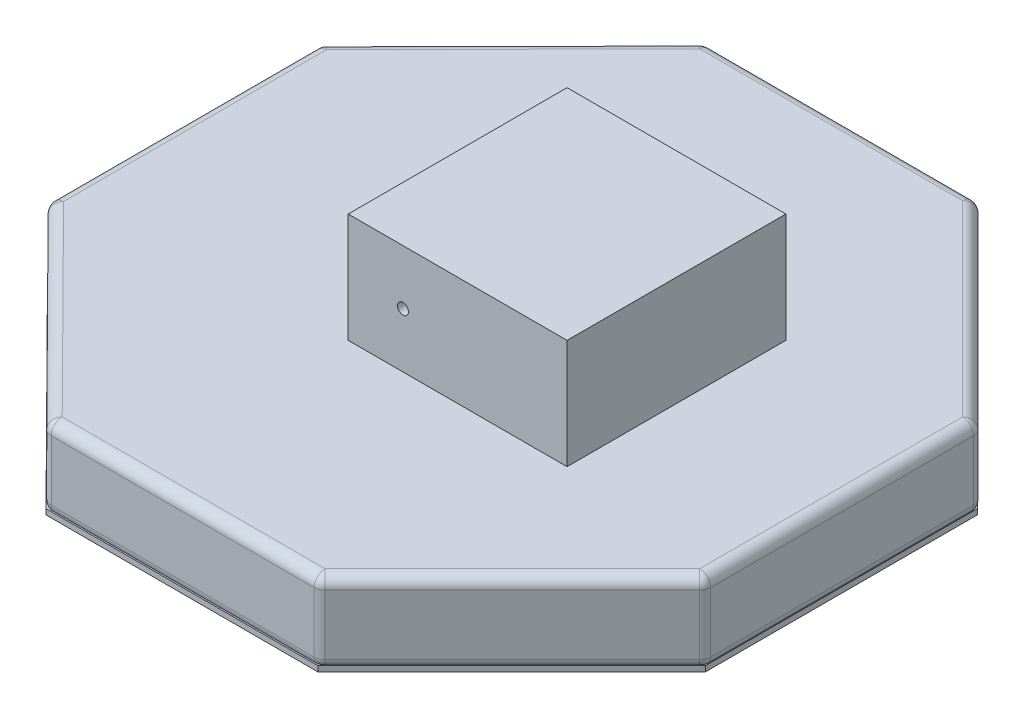
SolidWorks part; units mm, degrees
ref_plane "Front Plane" through (0, 0, 0) normal (0, 0, 1) x (1, 0, 0)
ref_plane "Top Plane" through (0, 0, 0) normal (0, 1, 0) x (1, 0, 0)
ref_plane "Right Plane" through (0, 0, 0) normal (1, 0, 0) x (0, 0, -1)
sketch "Sketch1" plane through (0, 0, 0) normal (0, 1, 0) x (1, 0, 0)
  line L5 (-60.1311, -24.8528) -> (-24.9839, -60.2623)
  line L6 (-24.9839, -60.2623) -> (24.7217, -60.2623)
  line L8 (24.7217, -60.2623) -> (60.1311, -24.8528)
  line L15 (60.1311, -24.8528) -> (60.1311, 24.8528)
  line L16 (24.7217, 60.2623) -> (60.1311, 24.8528)
  line L17 (-24.9839, 60.2623) -> (24.7217, 60.2623)
  line L18 (-60.1311, 24.8528) -> (-24.9839, 60.2623)
  line L19 (-60.1311, 24.8528) -> (-60.1311, -24.8528)
  point P0 (0, 0)
  point P1 (-0.1311, 0)
  point P2 (-0.1311, 0)
  point P3 (-0.1311, 0)
  point P4 (-0.1311, 0)
  point P6 (-0.1311, 0)
  point P9 (-42.5575, -42.5575)
  point P11 (-0.1311, -60.2623)
  point P13 (42.4264, -42.5575)
  point P15 (60.1311, 0)
  point P17 (42.4264, 42.5575)
  point P19 (-0.1311, 60.2623)
  point P20 (-42.5575, 42.5575)
  point P22 (-60.1311, 0)
  dimension "D1" = 135.213
  dimension "D2" = 135.213
  dimension "D3" = 225.213
  dimension "D4" = 225
  dimension "D6" = 135
  dimension "D5" = 135
  dimension "D7" = 49.7056
  dimension "D8" = 135
  dimension "D9" = 134.787
  dimension "D10" = 60.2623
sketch "Sketch2" plane through (0, 0, 0) normal (0, 1, 0) x (1, 0, 0)
  line L4 (-60, -24.8528) -> (-24.8528, -60.2623)
  line L5 (-24.8528, -60.2623) -> (24.8528, -60.2623)
  line L6 (24.8528, -60.2623) -> (60.2623, -24.8528)
  line L7 (60.2623, -24.8528) -> (60.2623, 24.8528)
  line L8 (24.8528, 60.2623) -> (60.2623, 24.8528)
  line L9 (-24.8528, 60.2623) -> (24.8528, 60.2623)
  line L10 (-60, 24.8528) -> (-24.8528, 60.2623)
  line L11 (-60, 24.8528) -> (-60, -24.8528)
  point P4 (0, 0)
  point P8 (0, 0)
  point P11 (0, 0)
  point P12 (0, 0)
  point P15 (0, 0)
  point P18 (-42.4264, -42.5575)
  point P21 (0, -60.2623)
  point P24 (42.5575, -42.5575)
  point P27 (60.2623, 0)
  point P30 (42.5575, 42.5575)
  point P33 (0, 60.2623)
  point P36 (-42.4264, 42.5575)
  point P39 (-60, 0)
  dimension "D5" = 135.213
  dimension "D6" = 135.213
  dimension "D8" = 225
  dimension "D10" = 135
  dimension "D11" = 49.7056
extrude "Boss-Extrude2" add sketch "Sketch2" along normal blind 15
sketch "Sketch3" plane through (0, 15, 0) normal (0, 1, 0) x (1, 0, 0)
  line L1 (30, -20) -> (-10, -20)
  line L2 (30, -20) -> (30, 20)
  line L3 (30, 20) -> (-10, 20)
  line L4 (-10, 20) -> (-10, -20)
  point P4 (0, 0)
extrude "Boss-Extrude3" add sketch "Sketch3" along normal blind 20
fillet "Fillet2" radius 2 24 edges at (42.5575, 15, -42.5575) (0, 15, -60.2623) (-42.4264, 15, -42.5575) (-60, 15, 0) (-60, 7.5, 24.8528) (-60, 7.5, -24.8528) (-24.8528, 7.5, -60.2623) (24.8528, 7.5, -60.2623) (60.2623, 7.5, -24.8528) (-42.4264, 15, 42.5575) (-24.8528, 7.5, 60.2623) (60.2623, 15, 0) (60.2623, 7.5, 24.8528) (42.5575, 15, 42.5575) (24.8528, 7.5, 60.2623) (0, 15, 60.2623) (42.5575, 0, -42.5575) (60.2623, 0, 0) (42.5575, 0, 42.5575) (-42.4264, 0, 42.5575) (0, 0, 60.2623) (-60, 0, 0) (-42.4264, 0, -42.5575) (0, 0, -60.2623)
sketch "Sketch4" plane through (0, 0, 20) normal (0, 0, 1) x (1, 0, 0)
  line L0 (0, 0) -> (0, 35) construction
  line L1 (-10, 35) -> (30, 35) construction
  line L2 (-10, 25) -> (30, 25) construction
  line L3 (-10, 35) -> (-10, 15) construction
  line L4 (30, 35) -> (30, 15) construction
  circle A0 centre (0, 25) radius 1
extrude "Cut-Extrude1" cut sketch "Sketch4" against normal up to surface (40 mm away) up to face at (10, 25, -20)
extrude "Boss-Extrude4" add sketch "Sketch1" along normal blind 1
